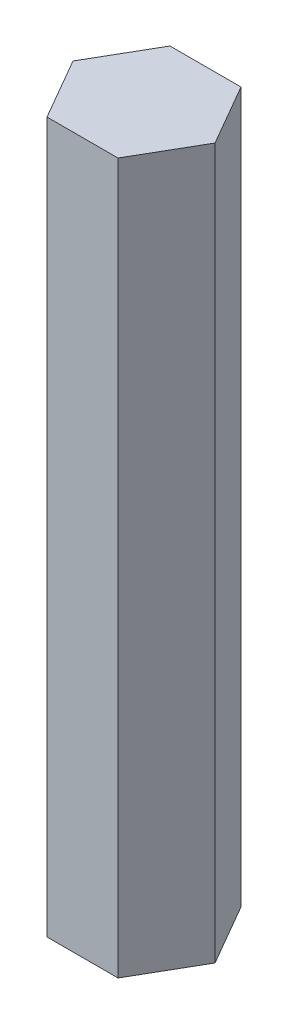
SolidWorks part; units mm, degrees
ref_plane "Front Plane" through (0, 0, 0) normal (0, 0, 1) x (1, 0, 0)
ref_plane "Top Plane" through (0, 0, 0) normal (0, 1, 0) x (1, 0, 0)
ref_plane "Right Plane" through (0, 0, 0) normal (1, 0, 0) x (0, 0, -1)
sketch "Sketch1" plane through (0, 0, 0) normal (0, 1, 0) x (1, 0, 0)
  line L1 (3, 0) -> (1.5, 2.5981)
  line L2 (1.5, 2.5981) -> (-1.5, 2.5981)
  line L3 (-1.5, 2.5981) -> (-3, 0)
  line L4 (-3, 0) -> (-1.5, -2.5981)
  line L5 (-1.5, -2.5981) -> (1.5, -2.5981)
  line L6 (1.5, -2.5981) -> (3, 0)
  circle A0 centre (0, 0) radius 2.5981 construction
  dimension "D1" = 3
extrude "Boss-Extrude1" add sketch "Sketch1" along normal blind 30
sketch "Sketch3" plane through (0, 0, 0) normal (0, -1, 0) x (1, 0, 0)
  circle A0 centre (0, 0) radius 1.6
  dimension "D1" = 3.2
extrude "Cut-Extrude1" cut sketch "Sketch3" against normal blind 5
